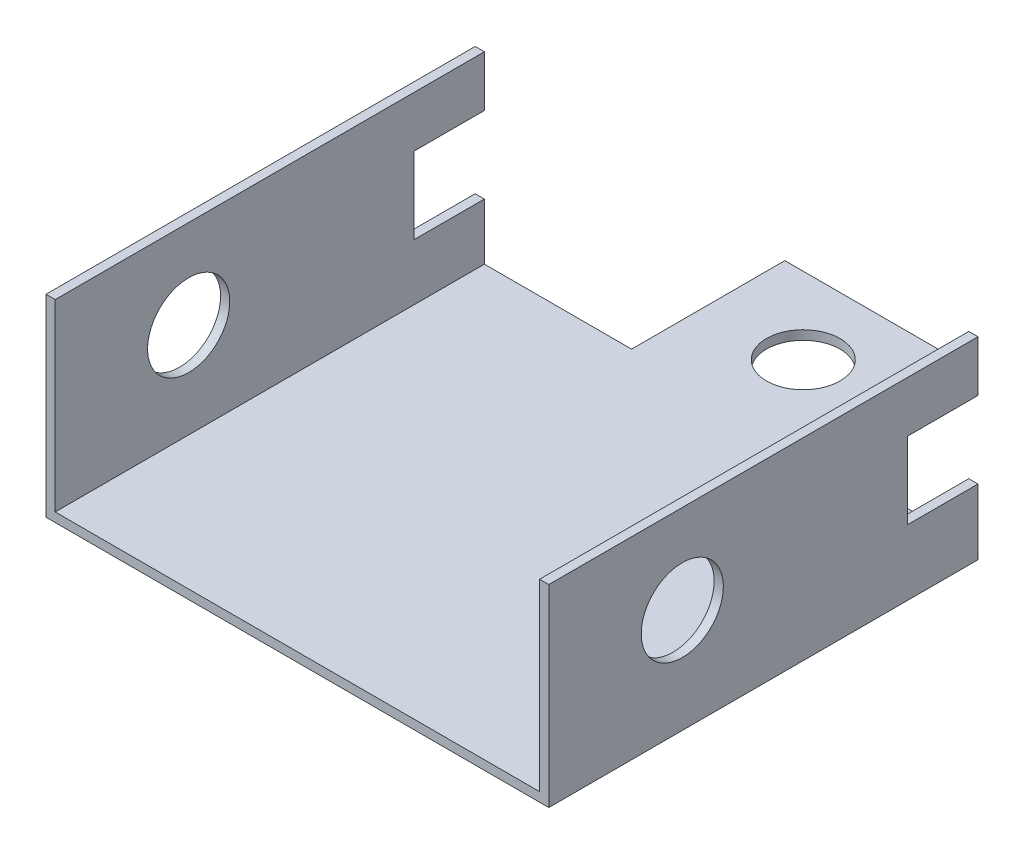
SolidWorks part; units mm, degrees
ref_plane "Front Plane" through (0, 0, 0) normal (0, 0, 1) x (1, 0, 0)
ref_plane "Top Plane" through (0, 0, 0) normal (0, 1, 0) x (1, 0, 0)
ref_plane "Right Plane" through (0, 0, 0) normal (1, 0, 0) x (0, 0, -1)
sketch "Sketch1" plane through (0, 0, 0) normal (0, 1, 0) x (1, 0, 0)
  line L1 (-27.7292, 11.93) -> (54.2708, 11.93)
  line L2 (-27.7292, 11.93) -> (-27.7292, -58.07)
  line L3 (-27.7292, -58.07) -> (54.2708, -58.07)
  line L4 (54.2708, 11.93) -> (54.2708, -58.07)
  dimension "D1" = 82
  dimension "D2" = 70
extrude "Boss-Extrude1" add sketch "Sketch1" along normal blind 1.5
sketch "Sketch2" plane through (0, 1.5, 0) normal (0, 1, 0) x (1, 0, 0)
  line L0 (54.2708, 11.93) -> (-27.7292, 11.93) construction
  line L1 (54.2708, 11.93) -> (52.7708, 11.93)
  line L2 (54.2708, 11.93) -> (54.2708, -58.07)
  line L3 (54.2708, -58.07) -> (52.7708, -58.07)
  line L4 (52.7708, 11.93) -> (52.7708, -58.07)
  line L5 (54.2708, -58.07) -> (54.2708, 11.93) construction
  line L6 (-27.7292, -58.07) -> (54.2708, -58.07) construction
  line L8 (-27.7292, 11.93) -> (-26.2292, 11.93)
  line L9 (-27.7292, 11.93) -> (-27.7292, -58.07)
  line L10 (-27.7292, -58.07) -> (-26.2292, -58.07)
  line L11 (-26.2292, 11.93) -> (-26.2292, -58.07)
  dimension "D1" = 1.5
  dimension "D2" = 1.5
extrude "Boss-Extrude2" add sketch "Sketch2" along normal blind 30
sketch "Sketch3" plane through (54.2708, 0, 0) normal (1, 0, 0) x (0, 0, -1)
  line L0 (11.93, 31.5) -> (11.93, 0) construction
  line L1 (11.93, 23.2) -> (0.43, 23.2)
  line L2 (11.93, 23.2) -> (11.93, 10.7)
  line L3 (11.93, 10.7) -> (0.43, 10.7)
  line L4 (0.43, 23.2) -> (0.43, 10.7)
  line L5 (-58.07, 31.5) -> (11.93, 31.5) construction
  line L6 (-58.07, 0) -> (11.93, 0) construction
  dimension "D1" = 11.5
  dimension "D2" = 8.3
  dimension "D3" = 12.5
  dimension "D4" = 10.7
extrude "Cut-Extrude1" cut sketch "Sketch3" against normal blind 90
sketch "Sketch4" plane through (54.2708, 0, 0) normal (1, 0, 0) x (0, 0, -1)
  line L1 (-58.07, 31.5) -> (11.93, 31.5) construction
  circle A0 centre (-36.3018, 17) radius 6.7
  dimension "D1" = 13.4
  dimension "D2" = 14.5
extrude "Cut-Extrude2" cut sketch "Sketch4" against normal blind 90
sketch "Sketch5" plane through (0, 1.5, 0) normal (0, 1, 0) x (1, 0, 0)
  line L0 (52.7708, 11.93) -> (-26.2292, 11.93) construction
  line L1 (-2.2292, 11.93) -> (28.7708, 11.93)
  line L2 (-2.2292, 11.93) -> (-2.2292, 36.93)
  line L3 (-2.2292, 36.93) -> (28.7708, 36.93)
  line L4 (28.7708, 11.93) -> (28.7708, 36.93)
  line L5 (54.2708, -58.07) -> (54.2708, 11.93) construction
  line L6 (-27.7292, 11.93) -> (-27.7292, -58.07) construction
  circle A0 centre (13.2708, 24.43) radius 6
  point P6 (13.2708, 36.93)
  dimension "D5" = 12
  dimension "D1" = 25
  dimension "D2" = 31
  dimension "D3" = 41
  dimension "D4" = 41
extrude "Boss-Extrude3" add sketch "Sketch5" against normal blind 1.5
